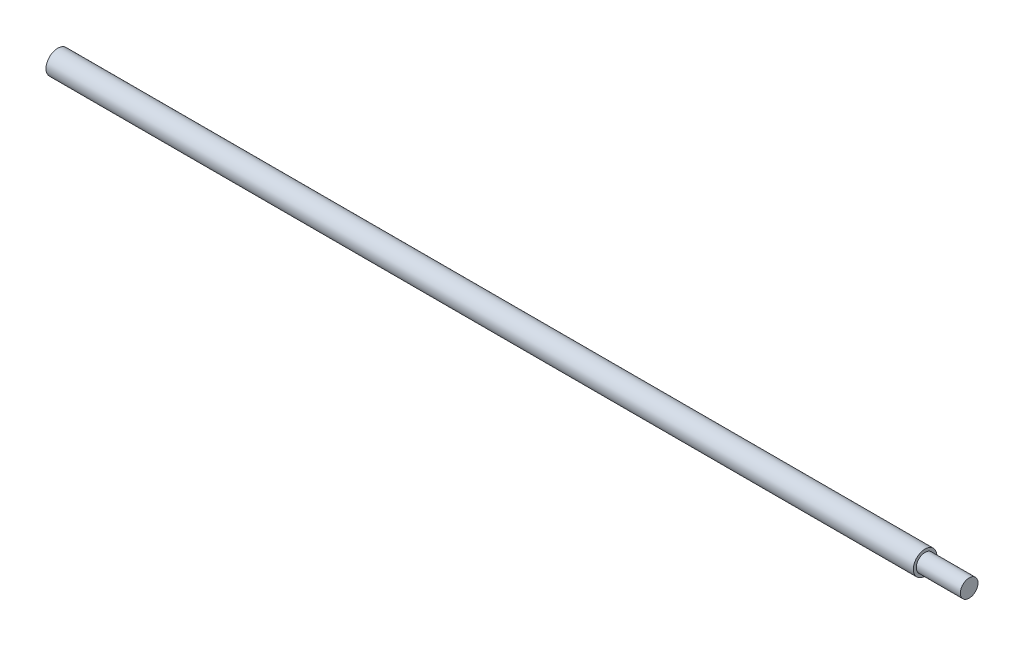
SolidWorks part; units mm, degrees
ref_plane "Front Plane" through (0, 0, 0) normal (0, 0, 1) x (1, 0, 0)
ref_plane "Top Plane" through (0, 0, 0) normal (0, 1, 0) x (1, 0, 0)
ref_plane "Right Plane" through (0, 0, 0) normal (1, 0, 0) x (0, 0, -1)
sketch "Sketch1" plane through (0, 0, 0) normal (0, 0, 1) x (1, 0, 0)
  line L0 (-155, 0) -> (-155, 4)
  line L1 (-155, 4) -> (140, 4)
  line L2 (140, 4) -> (140, 3)
  line L3 (140, 3) -> (155, 3)
  line L4 (155, 3) -> (155, 0)
  line L5 (155, 0) -> (-155, 0)
  line L6 (277.0819, 0) -> (-277.0819, 0) construction
  line L7 (0, -63.7054) -> (0, 63.7054) construction
  point P10 (0, 0)
  point P14 (0, 0)
  dimension "D1" = 310
  dimension "D2" = 15
  dimension "D3" = 8
  dimension "D4" = 6
revolve "Revolve1" add sketch "Sketch1" angle 360 about L6
cosmetic thread "Cosmetic Thread1" parameters "D2"=7
cosmetic thread "Cosmetic Thread2" parameters "D2"=5
